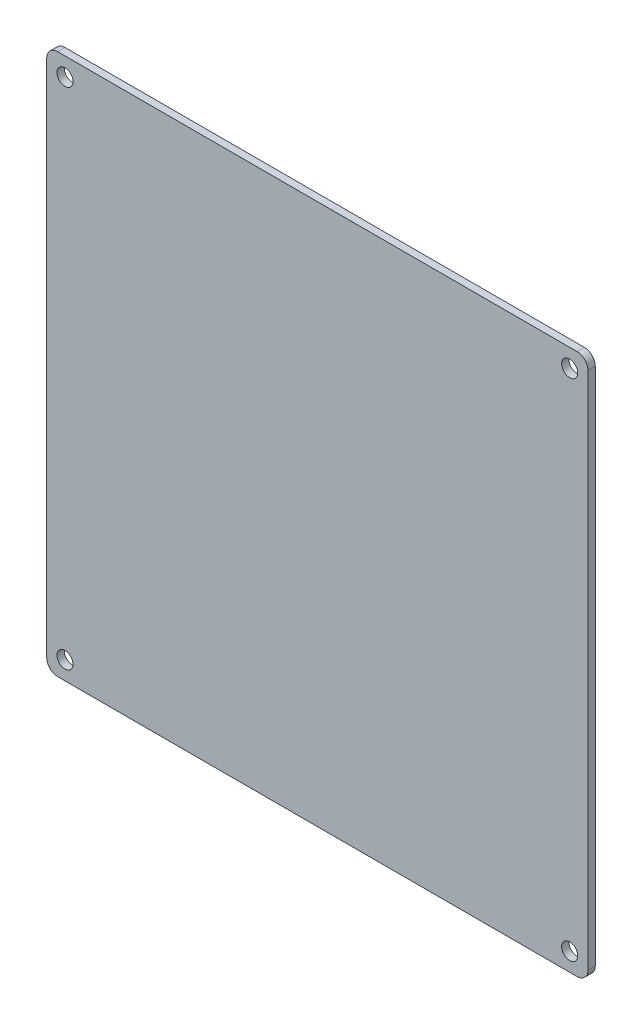
SolidWorks part; units mm, degrees
ref_plane "前视基准面" through (0, 0, 0) normal (0, 0, 1) x (1, 0, 0)
ref_plane "上视基准面" through (0, 0, 0) normal (0, 1, 0) x (1, 0, 0)
ref_plane "右视基准面" through (0, 0, 0) normal (1, 0, 0) x (0, 0, -1)
other "Configuration Table"
sketch "草图1" plane through (0, 0, 0) normal (0, 0, 1) x (1, 0, 0)
  line L1 (-37, -37) -> (37, -37)
  line L2 (-37, -37) -> (-37, 37)
  line L3 (-37, 37) -> (37, 37)
  line L4 (37, -37) -> (37, 37)
  line L5 (-37, -37) -> (37, 37) construction
  line L6 (-37, 37) -> (37, -37) construction
  line L7 (-34.5, -34.5) -> (34.5, -34.5) construction
  line L8 (-34.5, -34.5) -> (-34.5, 34.5) construction
  line L9 (-34.5, 34.5) -> (34.5, 34.5) construction
  line L10 (34.5, -34.5) -> (34.5, 34.5) construction
  line L11 (-34.5, -34.5) -> (34.5, 34.5) construction
  line L12 (-34.5, 34.5) -> (34.5, -34.5) construction
  circle A0 centre (-34.5, 34.5) radius 1.1
  circle A1 centre (34.5, 34.5) radius 1.1
  circle A2 centre (34.5, -34.5) radius 1.1
  circle A3 centre (-34.5, -34.5) radius 1.1
  point P0 (0, 0)
  point P6 (0, 0)
  dimension "D3" = 2.2
  dimension "D1" = 74
  dimension "D2" = 69
extrude "凸台-拉伸1" add sketch "草图1" along normal blind 1
fillet "圆角1" radius 1.5 4 edges at (-37, -37, 0.5) (37, -37, 0.5) (37, 37, 0.5) (-37, 37, 0.5)
